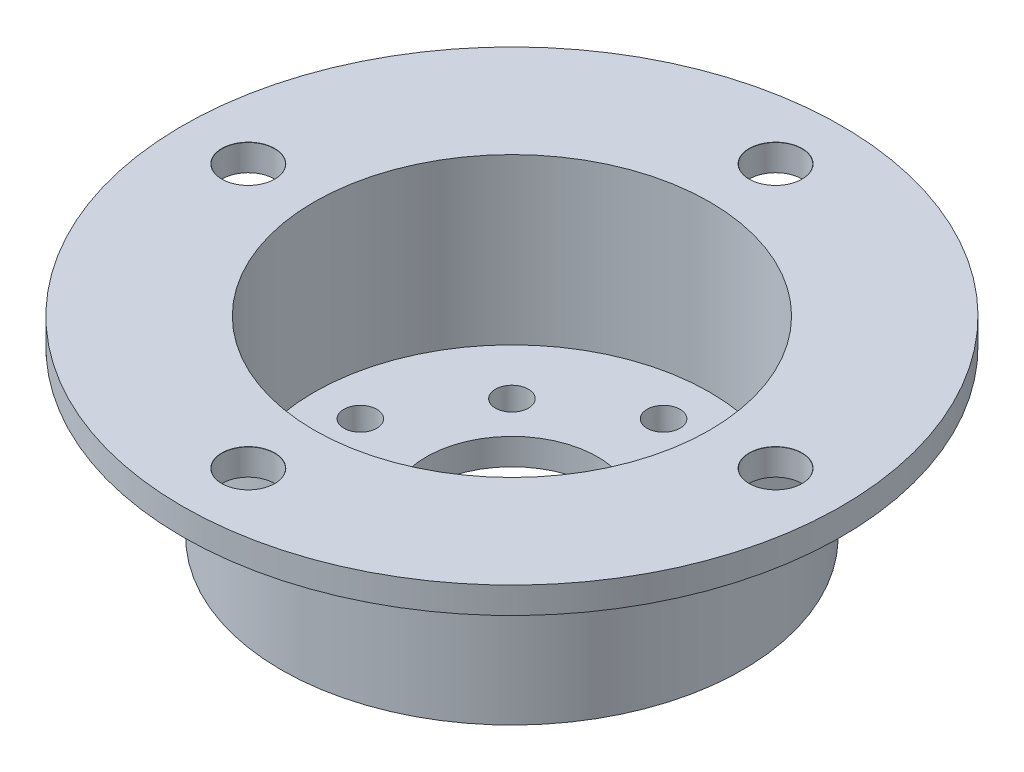
SolidWorks part; units mm, degrees
ref_plane "前视基准面" through (0, 0, 0) normal (0, 0, 1) x (1, 0, 0)
ref_plane "上视基准面" through (0, 0, 0) normal (0, 1, 0) x (1, 0, 0)
ref_plane "右视基准面" through (0, 0, 0) normal (1, 0, 0) x (0, 0, -1)
other "Configuration Table"
sketch "Sketch1" plane through (0, 0, 0) normal (0, 1, 0) x (1, 0, 0)
  circle A0 centre (0, 0) radius 13
  circle A1 centre (0, 0) radius 35
  dimension "D1" = 26
  dimension "D2" = 70
extrude "Boss-Extrude1" add sketch "Sketch1" against normal blind 4
sketch "Sketch2" plane through (0, -4, 0) normal (0, -1, 0) x (1, 0, 0)
  point P0 (0, 23)
  point P1 (-23, 0)
  point P2 (0, 0)
  point P4 (0, 0)
  dimension "D1" = 23
  dimension "D2" = 23
hole_wizard "Ø5.0 mm Dowel Holes1" positions "3DSketch1" profile "Sketch3" hole size "Ø5.0" standard "JIS"
sketch3d "3DSketch1"
  point P0 (0, -4, 23)
  point P3 (-23, -4, 0)
sketch "Sketch3" plane through (0, -4, 23) normal (1, 0, 0) x (0, 0, -1)
  line L0 (0, 0) -> (0, 21.5022)
  line L1 (0, 21.5022) -> (2.5, 20)
  line L2 (2.5, 20) -> (2.5, 0.025)
  line L3 (2.5, 0.025) -> (2.525, 0)
  line L5 (2.525, 0) -> (0, 0)
  line L6 (-2.5, 0.025) -> (-2.525, 0) construction
  line L10 (0, 21.5022) -> (-2.5, 20) construction
  line L11 (0, -6.35) -> (0, 107.95) construction
  dimension "Hole Dia." = 5
  dimension "Hole Depth" = 20
  dimension "Near C'Sink Dia." = 5.05
  dimension "Near C'Sink Angle" = 90
  dimension "Drill Angle" = 118
mirror "Mirror1" about plane through (0, 0, 0) normal (1, 0, 0) of "Ø5.0 mm Dowel Holes1" second plane through (0, 0, 0) second plane normal (0, 0, 1)
sketch "Sketch4" plane through (0, -4, 0) normal (0, -1, 0) x (1, 0, 0)
  point P0 (-14.1421, 14.1421)
  point P1 (14.1421, 14.1421)
  dimension "D1" = 90
  dimension "D2" = 45
  dimension "D3" = 20
  dimension "D4" = 20
hole_wizard "Ø5.0 mm Dowel Holes2" positions "3DSketch2" profile "Sketch5" hole size "Ø5.0" standard "JIS"
sketch3d "3DSketch2"
  point P0 (-14.1421, -4, 14.1421)
  point P3 (14.1421, -4, 14.1421)
sketch "Sketch5" plane through (-14.1421, -4, 14.1421) normal (1, 0, 0) x (0, 0, -1)
  line L0 (0, 0) -> (0, 21.5022)
  line L1 (0, 21.5022) -> (2.5, 20)
  line L2 (2.5, 20) -> (2.5, 0.025)
  line L3 (2.5, 0.025) -> (2.525, 0)
  line L5 (2.525, 0) -> (0, 0)
  line L6 (-2.5, 0.025) -> (-2.525, 0) construction
  line L10 (0, 21.5022) -> (-2.5, 20) construction
  line L11 (0, -6.35) -> (0, 107.95) construction
  dimension "Hole Dia." = 5
  dimension "Hole Depth" = 20
  dimension "Near C'Sink Dia." = 5.05
  dimension "Near C'Sink Angle" = 90
  dimension "Drill Angle" = 118
mirror "Mirror2" about plane through (0, 0, 0) normal (0, 0, 1) of "Ø5.0 mm Dowel Holes2"
sketch "Sketch6" plane through (0, 0, 0) normal (0, 1, 0) x (1, 0, 0)
  circle A0 centre (0, 0) radius 30
  circle A1 centre (0, 0) radius 35
  dimension "D1" = 60
  dimension "D2" = 70
extrude "Boss-Extrude2" add sketch "Sketch6" along normal blind 21
sketch "Sketch7" plane through (0, 21, 0) normal (0, 1, 0) x (1, 0, 0)
  circle A0 centre (0, 0) radius 30
  circle A1 centre (0, 0) radius 50
  dimension "D1" = 60
  dimension "D2" = 100
extrude "Boss-Extrude3" add sketch "Sketch7" along normal blind 4
sketch "Sketch8" plane through (0, 25, 0) normal (0, 1, 0) x (1, 0, 0)
  point P0 (0, 40)
  point P1 (-40, 0)
  point P2 (0, 0)
  point P4 (0, 0)
  dimension "D1" = 40
  dimension "D2" = 40
hole_wizard "Ø8.0 mm Dowel Holes1" positions "3DSketch3" profile "Sketch9" hole size "Ø8.0" standard "JIS"
sketch3d "3DSketch3"
  point P0 (0, 25, -40)
  point P3 (-40, 25, 0)
sketch "Sketch9" plane through (0, 25, -40) normal (1, 0, 0) x (0, 0, 1)
  line L0 (0, 0) -> (0, 22.4034)
  line L1 (0, 22.4034) -> (4, 20)
  line L2 (4, 20) -> (4, 0.025)
  line L3 (4, 0.025) -> (4.025, 0)
  line L5 (4.025, 0) -> (0, 0)
  line L6 (-4, 0.025) -> (-4.025, 0) construction
  line L10 (0, 22.4034) -> (-4, 20) construction
  line L11 (0, -6.35) -> (0, 107.95) construction
  dimension "Hole Dia." = 8
  dimension "Hole Depth" = 20
  dimension "Near C'Sink Dia." = 8.05
  dimension "Near C'Sink Angle" = 90
  dimension "Drill Angle" = 118
mirror "Mirror3" about plane through (0, 0, 0) normal (1, 0, 0) of "Ø8.0 mm Dowel Holes1" second plane through (0, 0, 0) second plane normal (0, 0, 1)
